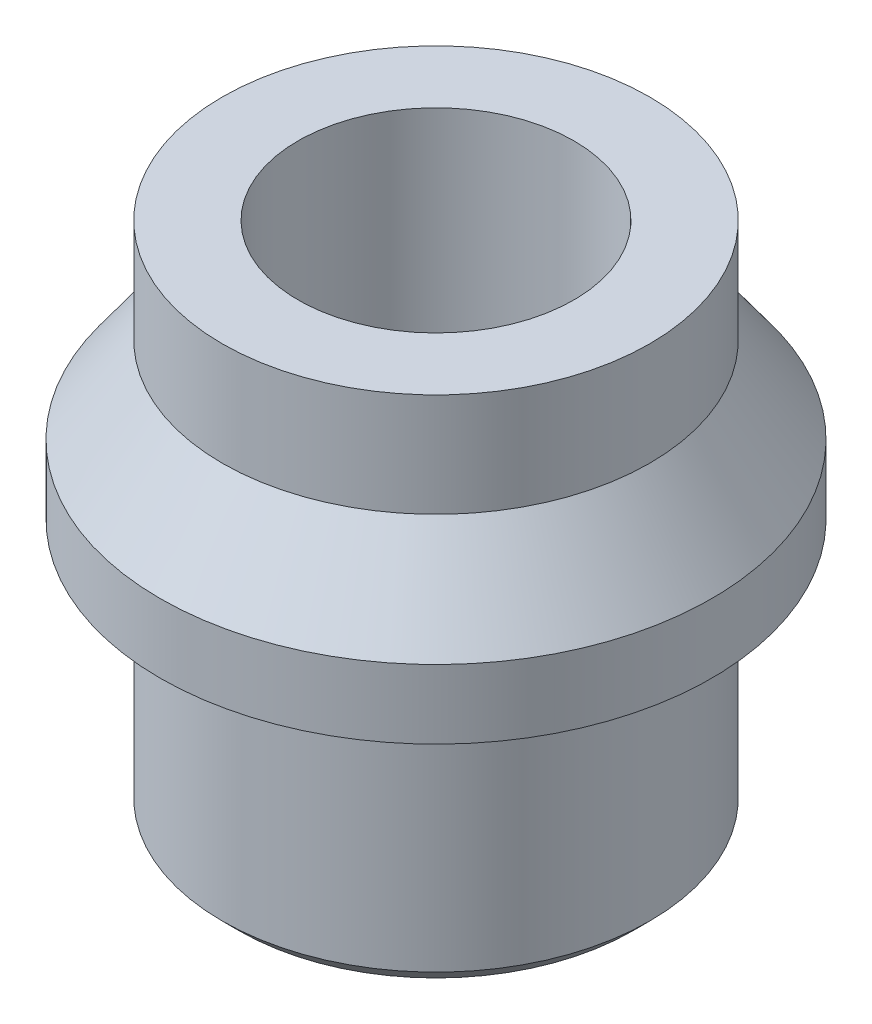
SolidWorks part; units mm, degrees
ref_plane "Front Plane" through (0, 0, 0) normal (0, 0, 1) x (1, 0, 0)
ref_plane "Top Plane" through (0, 0, 0) normal (0, 1, 0) x (1, 0, 0)
ref_plane "Right Plane" through (0, 0, 0) normal (1, 0, 0) x (0, 0, -1)
sketch "Sketch1" plane through (0, 0, 0) normal (0, 0, 1) x (1, 0, 0)
  line L0 (0, 0) -> (0, 15) construction
  line L1 (4, 0) -> (6.2, 0)
  line L2 (6.2, 0) -> (6.2, 7.5)
  line L3 (6.2, 7.5) -> (8, 7.5)
  line L4 (8, 7.5) -> (8, 9.5)
  line L5 (8, 9.5) -> (6.2, 12)
  line L6 (6.2, 12) -> (6.2, 15)
  line L7 (6.2, 15) -> (4, 15)
  line L8 (4, 15) -> (4, 0)
  dimension "D1" = 15
  dimension "D2" = 4
  dimension "D3" = 6.2
  dimension "D4" = 8
  dimension "D5" = 6.2
  dimension "D6" = 7.5
  dimension "D7" = 15
  dimension "D8" = 3
  dimension "D9" = 2
revolve "Revolve1" add sketch "Sketch1" angle 360 about L0
chamfer "Chamfer1" distance 0.5 angle 45 2 edges at (0, 0, -4) (0, 0, -6.2)
